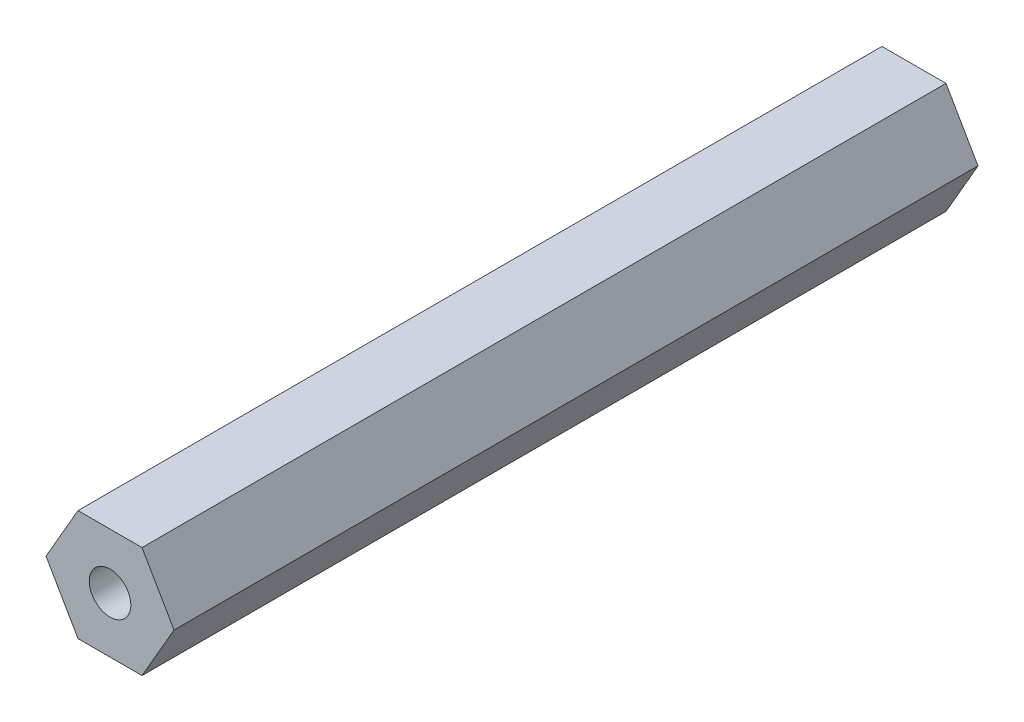
SolidWorks part; units mm, degrees
ref_plane "Alzado" through (0, 0, 0) normal (0, 0, 1) x (1, 0, 0)
ref_plane "Planta" through (0, 0, 0) normal (0, 1, 0) x (1, 0, 0)
ref_plane "Vista lateral" through (0, 0, 0) normal (1, 0, 0) x (0, 0, -1)
sketch "Croquis1" plane through (0, 0, 0) normal (0, 0, 1) x (1, 0, 0)
  line L1 (4.6188, 0) -> (2.3094, 4)
  line L2 (2.3094, 4) -> (-2.3094, 4)
  line L3 (-2.3094, 4) -> (-4.6188, 0)
  line L4 (-4.6188, 0) -> (-2.3094, -4)
  line L5 (-2.3094, -4) -> (2.3094, -4)
  line L6 (2.3094, -4) -> (4.6188, 0)
  circle A0 centre (0, 0) radius 4 construction
  circle A1 centre (0, 0) radius 1.5
  dimension "D2" = 3
  dimension "D1" = 8
extrude "Saliente-Extruir1" add sketch "Croquis1" along normal mid plane 58
